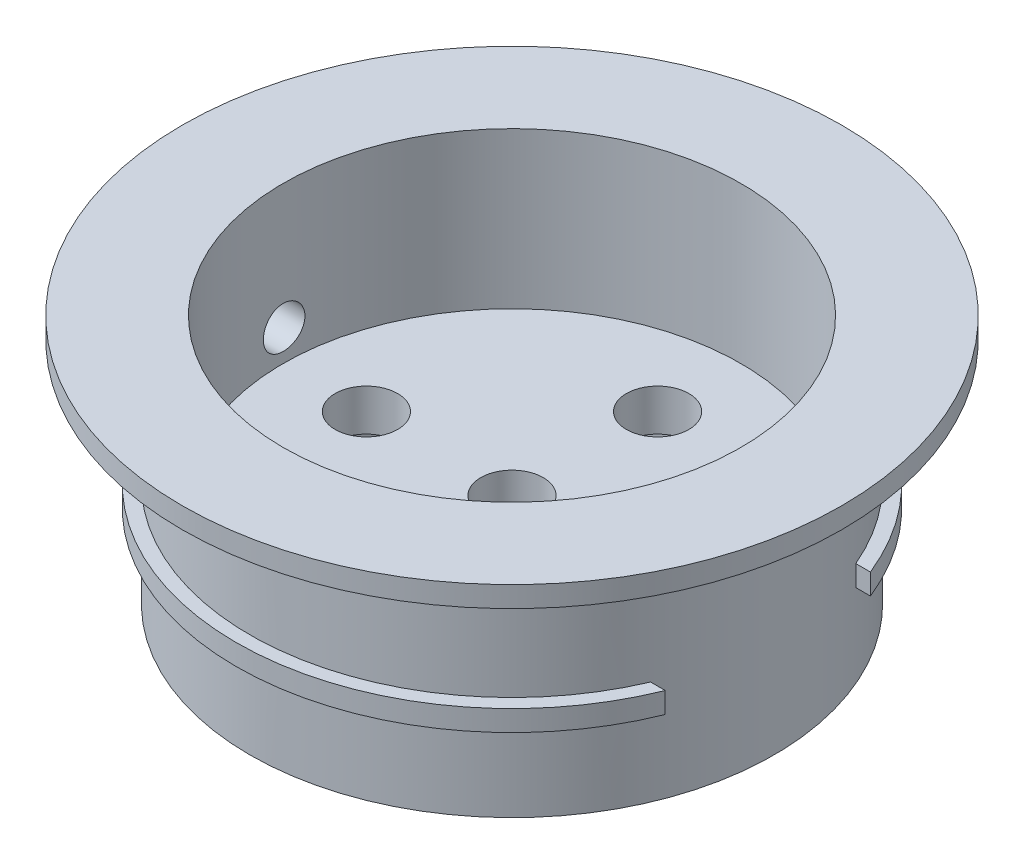
SolidWorks part; units mm, degrees
ref_plane "前视基准面" through (0, 0, 0) normal (0, 0, 1) x (1, 0, 0)
ref_plane "上视基准面" through (0, 0, 0) normal (0, 1, 0) x (1, 0, 0)
ref_plane "右视基准面" through (0, 0, 0) normal (1, 0, 0) x (0, 0, -1)
sketch "草图1" plane through (0, 0, 0) normal (0, 1, 0) x (1, 0, 0)
  circle A0 centre (0, 0) radius 15.85
  dimension "D1" = 31.7
extrude "凸台-拉伸1" add sketch "草图1" along normal blind 12
sketch "草图2" plane through (0, 0, 0) normal (0, -1, 0) x (1, 0, 0)
  circle A0 centre (0, 0) radius 10.1
  dimension "D1" = 20.2
extrude "切除-拉伸1" cut sketch "草图2" against normal blind 2.5
sketch "草图3" plane through (0, 12, 0) normal (0, 1, 0) x (1, 0, 0)
  circle A0 centre (0, 0) radius 11
  dimension "D1" = 22
extrude "切除-拉伸2" cut sketch "草图3" against normal blind 7.5
sketch "草图4" plane through (0, 2.5, 0) normal (0, -1, 0) x (1, 0, 0)
  circle A0 centre (0, 7) radius 1.5
  circle A1 centre (7, 0) radius 1.5
  circle A2 centre (0, -7) radius 1.5
  circle A3 centre (-7, 0) radius 1.5
  circle A4 centre (0, 0) radius 1.5
  point P12 (0, 0)
  dimension "D1" = 3
  dimension "D4" = 3
  dimension "D2" = 7
  dimension "D3" = 4
extrude "切除-拉伸3" cut sketch "草图4" against normal blind 6
ref_axis "基准轴1" through (0, -0.5, 0) along (0, 1, 0)
sketch "草图5" plane through (0, 0, 0) normal (1, 0, 0) x (0, 0, -1)
  line L0 (-15.35, 11) -> (-12.6, 9.4123)
  line L1 (-12.6, 9.4123) -> (-12.6, 0)
  line L2 (17.435, 0) -> (-17.435, 0) construction
  line L3 (-12.6, 0) -> (-15.85, 0)
  line L4 (-15.85, 12) -> (-15.85, 0) construction
  line L5 (-15.85, 0) -> (-15.85, 11)
  line L6 (0, 6.6) -> (0, -6.6) construction
  line L7 (15.85, 12) -> (-15.85, 12) construction
  line L8 (-15.35, 11) -> (-15.85, 11)
  dimension "D1" = 12.6
  dimension "D2" = 30
  dimension "D3" = 0.5
  dimension "D4" = 1
revolve "切除-旋转1" cut sketch "草图5" angle 360 about axis through (0, -0.5, 0) along (0, 1, 0)
ref_plane "基准面1" through (0, 4, 0) normal (0, 1, 0) x (1, 0, 0)
sketch "草图6" plane through (0, 4, 0) normal (0, 1, 0) x (1, 0, 0)
  line L1 (11.4858, 4.9323) -> (12.2978, 4.9323)
  line L2 (-6.6, 0) -> (6.6, 0) construction
  line L3 (11.4858, -4.9323) -> (12.2978, -4.9323)
  arc A0 (11.4858, 4.9323) -> (11.4858, -4.9323) centre (0, 0) ccw
  arc A1 (12.2978, 4.9323) -> (12.2978, -4.9323) centre (0, 0) ccw
  dimension "D1" = 26.5
  dimension "D2" = 25
extrude "凸台-拉伸2" add sketch "草图6" along normal blind 1
sketch "草图7" plane through (0, 0, 0) normal (1, 0, 0) x (0, 0, -1)
  line L0 (0, 6.6) -> (0, -6.6) construction
  line L1 (17.435, 0) -> (-17.435, 0) construction
  circle A0 centre (0, 6) radius 1
  dimension "D1" = 2
  dimension "D2" = 6
extrude "切除-拉伸4" cut sketch "草图7" against normal blind 16
